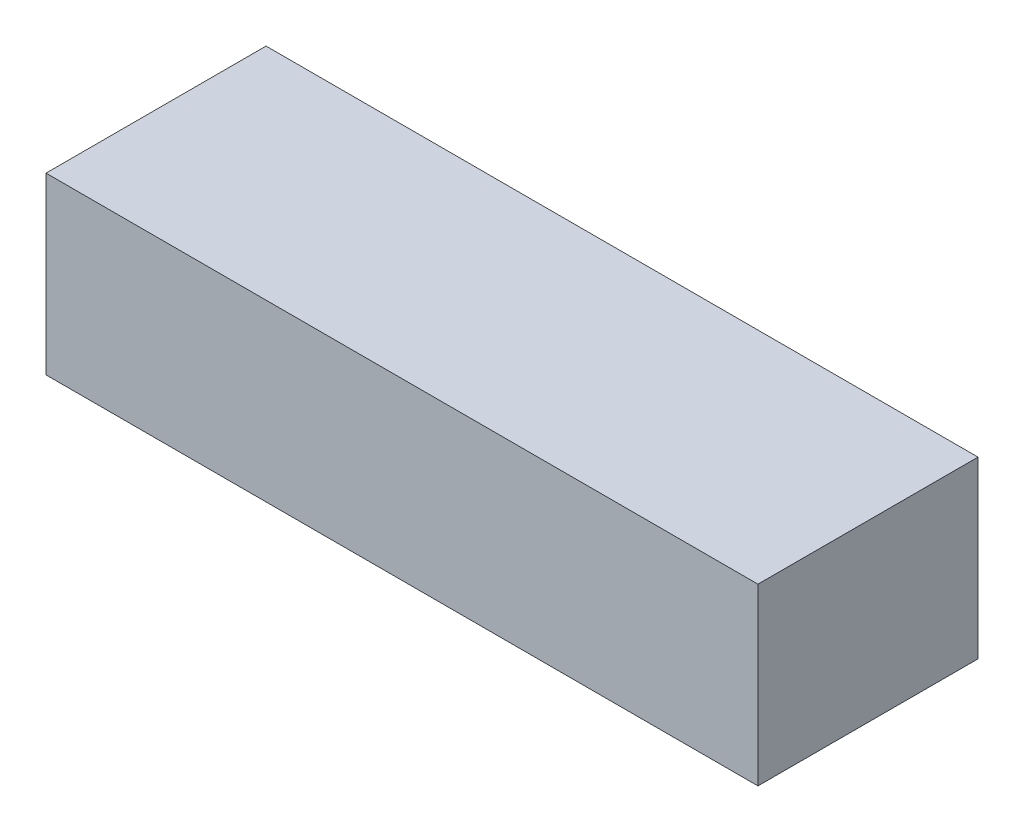
SolidWorks part; units mm, degrees
ref_plane "前视基准面" through (0, 0, 0) normal (0, 0, 1) x (1, 0, 0)
ref_plane "上视基准面" through (0, 0, 0) normal (0, 1, 0) x (1, 0, 0)
ref_plane "右视基准面" through (0, 0, 0) normal (1, 0, 0) x (0, 0, -1)
other "Configuration Table"
sketch "草图1" plane through (0, 0, 0) normal (0, 1, 0) x (1, 0, 0)
  line L1 (-55, 17) -> (55, 17)
  line L2 (-55, 17) -> (-55, -17)
  line L3 (-55, -17) -> (55, -17)
  line L4 (55, 17) -> (55, -17)
  line L5 (-55, 17) -> (55, -17) construction
  line L6 (-55, -17) -> (55, 17) construction
  point P0 (0, 0)
  dimension "D1" = 34
  dimension "D2" = 110
extrude "凸台-拉伸1" add sketch "草图1" along normal blind 27
